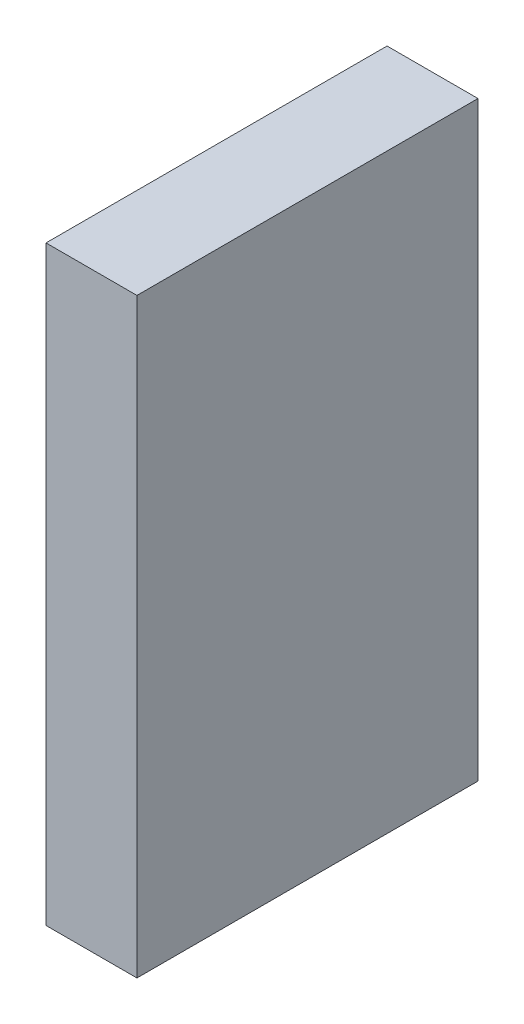
SolidWorks part; units mm, degrees
ref_plane "Спереди" through (0, 0, 0) normal (0, 0, 1) x (1, 0, 0)
ref_plane "Сверху" through (0, 0, 0) normal (0, 1, 0) x (1, 0, 0)
ref_plane "Справа" through (0, 0, 0) normal (1, 0, 0) x (0, 0, -1)
sketch "Эскиз1" plane through (0, 0, 0) normal (1, 0, 0) x (0, 0, -1)
  line L1 (-35.2993, 46.1801) -> (-20.2993, 46.1801)
  line L2 (-35.2993, 46.1801) -> (-35.2993, 20.1801)
  line L3 (-35.2993, 20.1801) -> (-20.2993, 20.1801)
  line L4 (-20.2993, 46.1801) -> (-20.2993, 20.1801)
  dimension "D1" = 15
  dimension "D2" = 26
extrude "Бобышка-Вытянуть1" add sketch "Эскиз1" along normal blind 4
